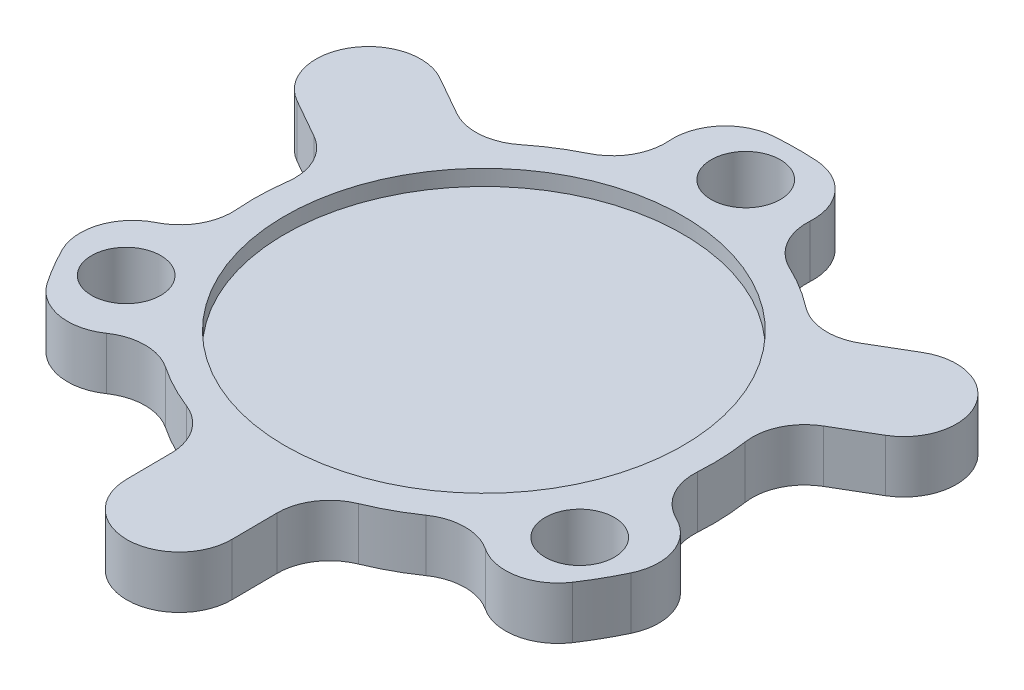
SolidWorks part; units mm, degrees
ref_plane "Спереди" through (0, 0, 0) normal (0, 0, 1) x (1, 0, 0)
ref_plane "Сверху" through (0, 0, 0) normal (0, 1, 0) x (1, 0, 0)
ref_plane "Справа" through (0, 0, 0) normal (1, 0, 0) x (0, 0, -1)
sketch "Sketch1" plane through (0, 0, 0) normal (0, 1, 0) x (1, 0, 0)
  circle A0 centre (0, 0) radius 19
  dimension "D1" = 38
extrude "Boss-Extrude1" add sketch "Sketch1" along normal blind 3.5
sketch "Sketch2" plane through (0, 0, 0) normal (0, 1, 0) x (1, 0, 0)
  circle A0 centre (0, 0) radius 30
  circle A1 centre (0, 0) radius 19
  circle A2 centre (0, 0) radius 25 construction
  circle A3 centre (0, 25) radius 3.3
  circle A4 centre (21.6506, -12.5) radius 3.3
  circle A5 centre (-21.6506, -12.5) radius 3.3
  point P16 (0, 0)
  dimension "D1" = 3
extrude "Boss-Extrude2" add sketch "Sketch2" along normal blind 5
sketch "Sketch3" plane through (0, 5, 0) normal (0, 1, 0) x (1, 0, 0)
  line L0 (0, 0) -> (-13.8376, 50.1433)
  line L1 (0, 0) -> (-44.8846, -12.3864)
  line L2 (-13.8376, 50.1433) -> (-44.8846, -12.3864)
  line L3 (50.3441, -13.0879) -> (11.7154, 45.0644)
  line L4 (0, 0) -> (11.7154, 45.0644)
  line L5 (0, 0) -> (50.3441, -13.0879)
  line L6 (-36.5066, -37.0553) -> (33.1692, -32.678)
  line L7 (0, 0) -> (33.1692, -32.678)
  line L8 (0, 0) -> (-36.5066, -37.0553)
  circle A0 centre (0, 0) radius 21.908
  point P12 (0, 0)
  circle M10 centre (0, 0) radius 30
  dimension "D1" = 3
extrude "Cut-Extrude1" cut sketch "Sketch3" against normal blind 10 contours L0 L2 L1 M10 | A0 L0 L1 M10 | L5 L3 L4 M10 | A0 L5 L4 M10 | L8 L6 L7 M10 | A0 L8 L7 M10
fillet "Fillet1" radius 5 6 edges at (15.6064, 2.5, 15.3753) (21.2032, 2.5, 5.5122) (5.5122, 2.5, -21.2032) (-15.3753, 2.5, 15.6064) (-21.1186, 2.5, 5.8279) (-5.8279, 2.5, -21.1186)
fillet "Fillet2" radius 5 6 edges at (-28.919, 2.5, 7.9805) (-21.0544, 2.5, 21.3709) (21.3709, 2.5, 21.0544) (29.0349, 2.5, 7.5482) (7.5482, 2.5, -29.0349) (-7.9805, 2.5, -28.919)
sketch "Sketch4" plane through (0, 5, 0) normal (0, 1, 0) x (1, 0, 0)
  line L0 (0, 0) -> (-19.0541, 10.8122) construction
  line L1 (-25.483, 14.4602) -> (-21.1343, 11.9926) construction
  line L2 (-23.0153, 18.8089) -> (-18.6667, 16.3412)
  line L3 (-27.9506, 10.1116) -> (-23.6019, 7.6439)
  line L4 (22.7322, 19.1502) -> (18.4208, 16.6179)
  line L5 (27.7966, 10.5274) -> (23.4853, 7.9952)
  line L6 (25.2644, 14.8388) -> (20.953, 12.3066) construction
  line L7 (5.2184, -29.2617) -> (5.1811, -24.2619)
  line L8 (-4.7813, -29.3363) -> (-4.8186, -24.3365)
  line L9 (0.2186, -29.299) -> (0.1813, -24.2992) construction
  arc A0 (-9.6506, 19.6679) -> (-21.8338, -1.8022) centre (0, 0) ccw construction
  arc A1 (-23.0153, 18.8089) -> (-27.9506, 10.1116) centre (-25.483, 14.4602) ccw
  arc A2 (-23.6019, 7.6439) -> (-18.6667, 16.3412) centre (-21.1343, 11.9926) ccw
  arc A3 (27.7966, 10.5274) -> (22.7322, 19.1502) centre (25.2644, 14.8388) ccw
  arc A4 (18.4208, 16.6179) -> (23.4853, 7.9952) centre (20.953, 12.3066) ccw
  arc A5 (-4.7813, -29.3363) -> (5.2184, -29.2617) centre (0.2186, -29.299) ccw
  arc A6 (5.1811, -24.2619) -> (-4.8186, -24.3365) centre (0.1813, -24.2992) ccw
  point P8 (-23.3086, 13.2264)
  point P14 (0, 0)
  point P17 (23.1087, 13.5727)
  point P24 (0.1999, -26.7991)
  point P29 (0, 0)
  dimension "D1" = 5
  dimension "D3" = 10
  dimension "D2" = 3
extrude "Boss-Extrude3" add sketch "Sketch4" against normal blind 5
fillet "Fillet3" radius 5 6 edges at (16.4467, 2.5, -14.4729) (20.6505, 2.5, -7.3157) (4.3106, 2.5, 21.4798) (-3.9896, 2.5, 21.5417) (-20.7573, 2.5, -7.0068) (-16.6608, 2.5, -14.226)
